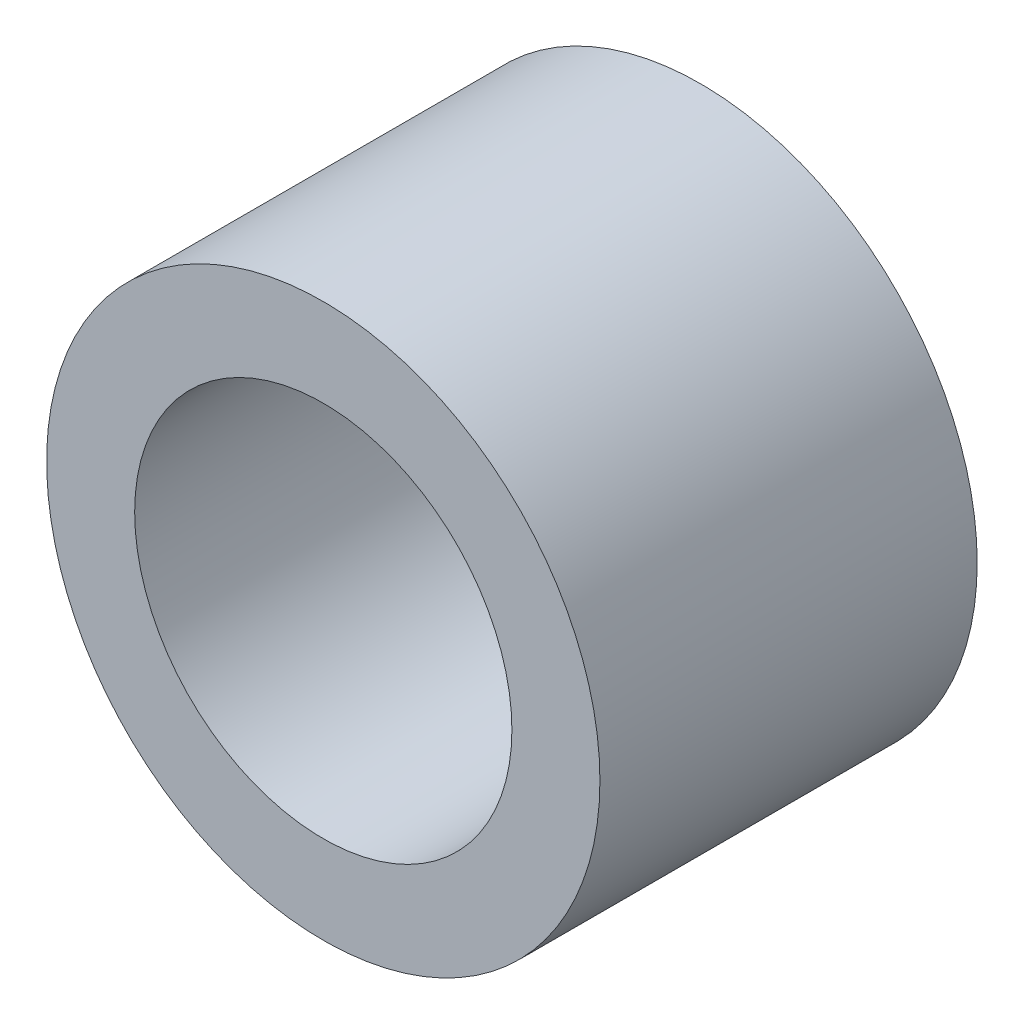
SolidWorks part; units mm, degrees
ref_plane "Plan de face" through (0, 0, 0) normal (0, 0, 1) x (1, 0, 0)
ref_plane "Plan de dessus" through (0, 0, 0) normal (0, 1, 0) x (1, 0, 0)
ref_plane "Plan de droite" through (0, 0, 0) normal (1, 0, 0) x (0, 0, -1)
sketch "Esquisse1" plane through (0, 0, 0) normal (0, 0, 1) x (1, 0, 0)
  circle A0 centre (0, 0) radius 2.2
  circle A1 centre (0, 0) radius 1.5
  dimension "D1" = 3
  dimension "D2" = 4.4
extrude "Boss.-Extru.1" add sketch "Esquisse1" along normal blind 3
